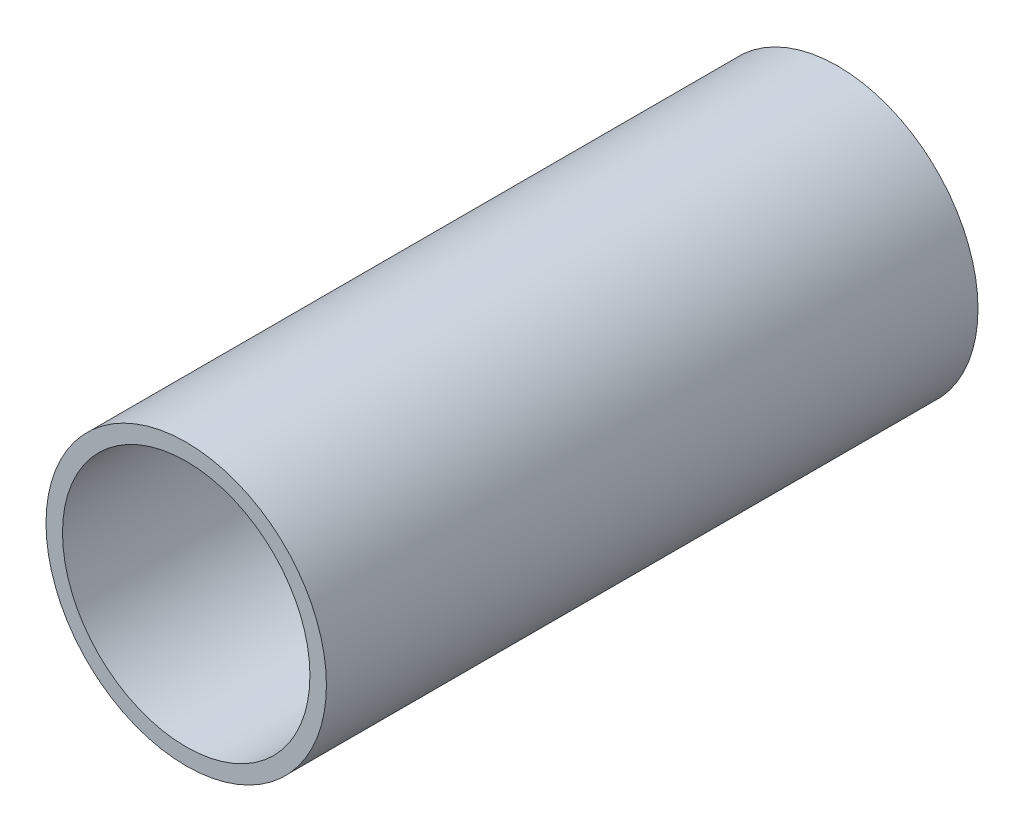
SolidWorks part; units mm, degrees
ref_plane "Ön Düzlem" through (0, 0, 0) normal (0, 0, 1) x (1, 0, 0)
ref_plane "Üst Düzlem" through (0, 0, 0) normal (0, 1, 0) x (1, 0, 0)
ref_plane "Sağ Düzlem" through (0, 0, 0) normal (1, 0, 0) x (0, 0, -1)
sketch "Sketch1" plane through (0, 0, 0) normal (0, 0, 1) x (1, 0, 0)
  circle A0 centre (0, 0) radius 85
  circle A1 centre (0, 0) radius 75
  dimension "D1" = 170
  dimension "D2" = 150
extrude "Boss-Extrude1" add sketch "Sketch1" along normal blind 395
